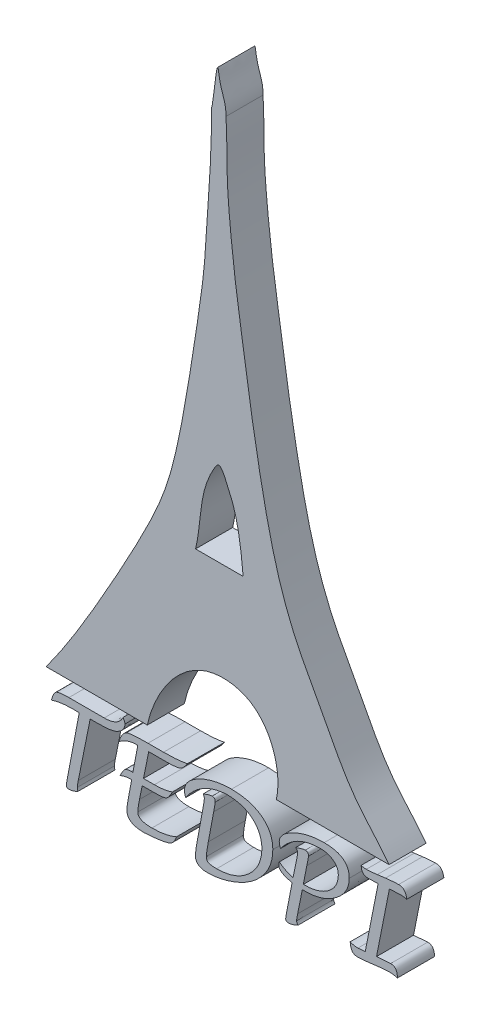
SolidWorks part; units mm, degrees
ref_plane "Plan de face" through (0, 0, 0) normal (0, 0, 1) x (1, 0, 0)
ref_plane "Plan de dessus" through (0, 0, 0) normal (0, 1, 0) x (1, 0, 0)
ref_plane "Plan de droite" through (0, 0, 0) normal (1, 0, 0) x (0, 0, -1)
sketch "Esquisse1" plane through (0, 0, 0) normal (0, 0, 1) x (-1, 0, 0)
  line L0 (178.3333, 695) -> (891.6667, 695) construction
  line L1 (-9.2535, 0) -> (-6.2099, 0)
  line L2 (-2.7289, 0) -> (0, 0)
  line L3 (-4.0317, -4.7681) -> (-5.3157, -4.7681)
  line L4 (335.1437, 1021) -> (1700.477, 1021) construction
  line L5 (0, 0) -> (0.232, 0) construction
  line L6 (0.232, 0) -> (0.232, 2.5042) construction
  line L7 (0.232, 2.5042) -> (-9.2535, 2.5042) construction
  line L8 (-335.8148, -1021.0254) -> (-1701.1482, -1021.0254) construction
  line L9 (-9.2535, 0) -> (-9.2535, 2.5042) construction
  spline S0 degree 3 poles (0, 0) (-0.2666, -0.3621) (-0.8684, -1.2716) (-1.8007, -2.8848) (-2.9549, -5.0092) (-3.5466, -6.5766) (-4.3141, -11.5703) (-4.2427, -11.5612) (-4.487, -14.3635) (-4.4555, -15.2841) knots 0.014515 0.014515 0.014515 0.014515 0.096269 0.212293 0.360312 0.504023 0.634638 0.815503 1 1 1 1
  spline S1 degree 3 poles (-4.4555, -15.2841) (-4.511, -15.3091) (-4.6055, -16.7288) (-4.6986, -15.8052) (-4.8633, -15.6137) (-4.851, -15.2841) knots 0 0 0 0 0.498353 0.61036 1 1 1 1
  spline S5 degree 3 poles (-4.851, -15.2841) (-4.8845, -14.8496) (-4.857, -14.0546) (-4.9519, -12.8858) (-5.0875, -11.603) (-5.3345, -10.0269) (-5.5663, -8.4757) (-5.8587, -6.913) (-6.1522, -5.5369) (-6.692, -3.9811) (-7.505, -2.5857) (-8.2218, -1.1225) (-8.9658, -0.3854) (-9.2535, 0) knots 0 0 0 0 0.080461 0.146709 0.216493 0.318839 0.441459 0.506316 0.612614 0.701349 0.809009 0.910911 1 1 1 1
  spline S6 degree 3 poles (-6.2099, 0) (-6.3645, -0.6512) (-5.9974, -2.0187) (-3.7604, -2.296) (-2.903, -0.8217) (-2.7289, 0) knots 0 0 0 0 0.357823 0.533217 1 1 1 1
  spline S7 degree 3 poles (-4.0317, -4.7681) (-4.215, -5.5494) (-4.091, -6.1874) (-4.6901, -7.1624) (-4.9014, -6.6441) (-5.1876, -6.0389) (-5.2771, -5.202) (-5.3157, -4.7681) knots 0 0 0 0 0.458128 0.496287 0.582631 0.670032 1 1 1 1
  text T0 "TEDPI" font "Lucida Handwriting" height 2.25
  point P24 (0, 0)
extrude "Boss.-Extru.1" add sketch "Esquisse1" along normal blind 1 contours L2 S0 S1 S5 L1 S6
